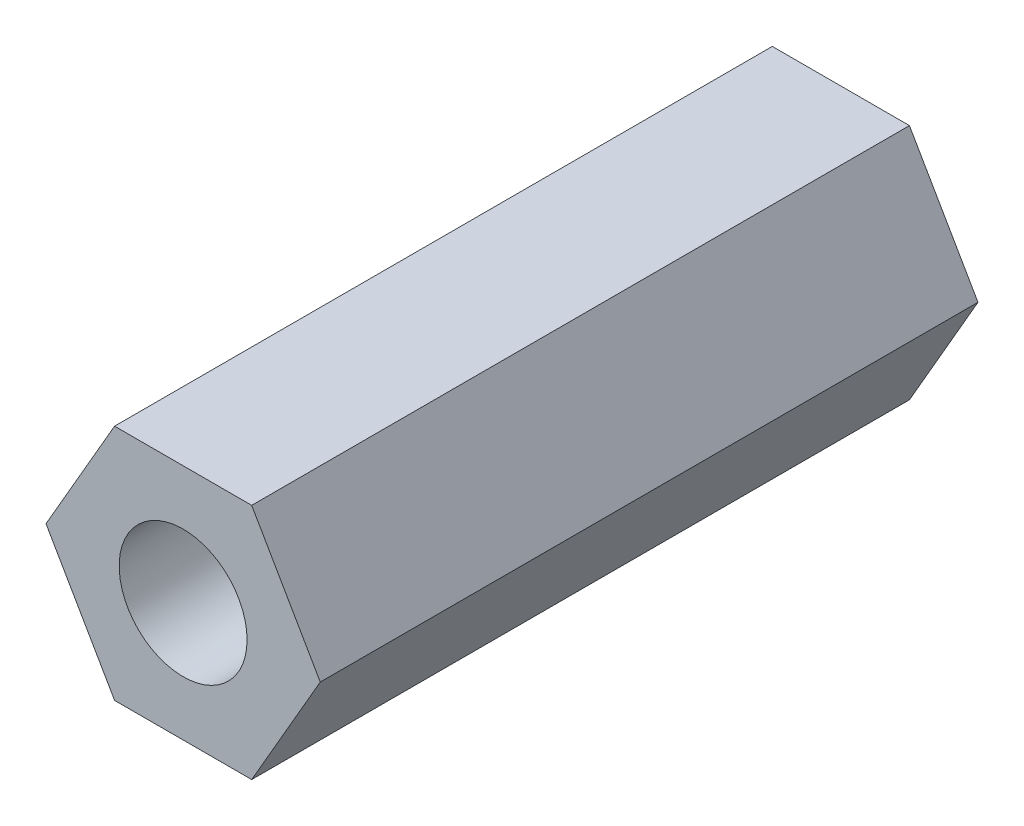
SolidWorks part; units mm, degrees
ref_plane "Alzado" through (0, 0, 0) normal (0, 0, 1) x (1, 0, 0)
ref_plane "Planta" through (0, 0, 0) normal (0, 1, 0) x (1, 0, 0)
ref_plane "Vista lateral" through (0, 0, 0) normal (1, 0, 0) x (0, 0, -1)
sketch "Croquis1" plane through (0, 0, 0) normal (0, 0, 1) x (1, 0, 0)
  line L1 (3.7528, 0) -> (1.8764, 3.25)
  line L2 (1.8764, 3.25) -> (-1.8764, 3.25)
  line L3 (-1.8764, 3.25) -> (-3.7528, 0)
  line L4 (-3.7528, 0) -> (-1.8764, -3.25)
  line L5 (-1.8764, -3.25) -> (1.8764, -3.25)
  line L6 (1.8764, -3.25) -> (3.7528, 0)
  circle A0 centre (0, 0) radius 1.75
  circle A1 centre (0, 0) radius 3.25 construction
  dimension "D1" = 3.5
  dimension "D2" = 1.5
extrude "Saliente-Extruir1" add sketch "Croquis1" along normal blind 18
